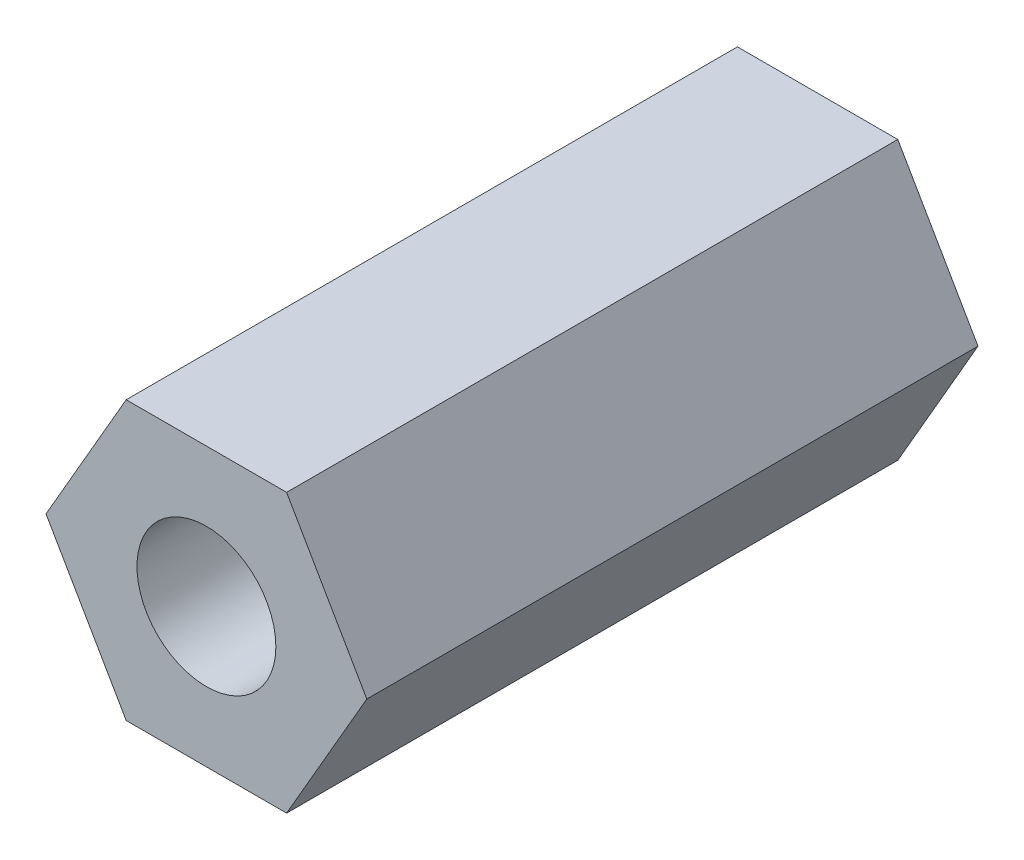
SolidWorks part; units mm, degrees
ref_plane "Front Plane" through (0, 0, 0) normal (0, 0, 1) x (1, 0, 0)
ref_plane "Top Plane" through (0, 0, 0) normal (0, 1, 0) x (1, 0, 0)
ref_plane "Right Plane" through (0, 0, 0) normal (1, 0, 0) x (0, 0, -1)
sketch "Sketch1" plane through (0, 0, 0) normal (0, 0, 1) x (1, 0, 0)
  line L0 (2.8868, 0) -> (1.4434, 2.5)
  line L1 (1.4434, 2.5) -> (-1.4434, 2.5)
  line L2 (-1.4434, 2.5) -> (-2.8868, 0)
  line L3 (-2.8868, 0) -> (-1.4434, -2.5)
  line L4 (-1.4434, -2.5) -> (1.4434, -2.5)
  line L5 (1.4434, -2.5) -> (2.8868, 0)
  circle A0 centre (0, 0) radius 1.25
extrude "Hex" add sketch "Sketch1" along normal blind 11
equation "\"af\"= 5mm"
equation "\"bore_d\"= 2.5mm"
equation "\"length\"= 11mm"
equation "\"D1@Hex\" = \"length\""
